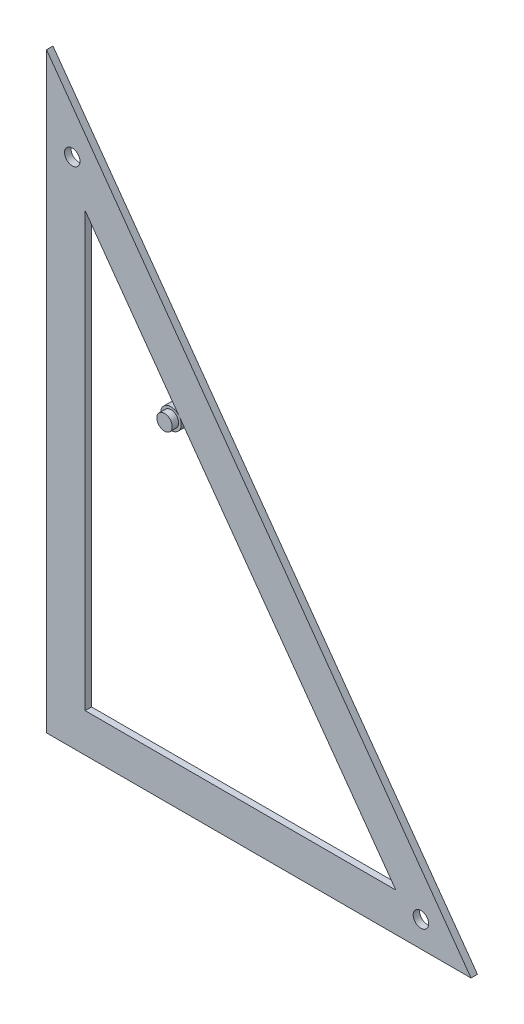
SolidWorks part; units mm, degrees
ref_plane "前视基准面" through (0, 0, 0) normal (0, 0, 1) x (1, 0, 0)
ref_plane "上视基准面" through (0, 0, 0) normal (0, 1, 0) x (1, 0, 0)
ref_plane "右视基准面" through (0, 0, 0) normal (1, 0, 0) x (0, 0, -1)
sketch "草图1" plane through (0, 0, 0) normal (0, 0, 1) x (1, 0, 0)
  line L0 (0, 0) -> (0, 460)
  line L1 (0, 460) -> (330, 0)
  line L2 (330, 0) -> (0, 0)
  line L3 (30, 30) -> (30, 366.7157)
  line L4 (30, 366.7157) -> (271.5569, 30)
  line L5 (271.5569, 30) -> (30, 30)
  circle A0 centre (20, 397.8105) radius 6
  circle A1 centre (291.0379, 20) radius 6
  dimension "D4" = 12
  dimension "D7" = 12
  dimension "D9" = 20
  dimension "D1" = 460
  dimension "D2" = 330
  dimension "D5" = 20
  dimension "D6" = 20
  dimension "D8" = 20
  dimension "D3" = 30
extrude "凸台-拉伸1" add sketch "草图1" along normal mid plane 5
sketch "草图2" plane through (0, 0, 0) normal (0, 0, 1) x (1, 0, 0)
  line L2 (271.5569, 30) -> (30, 366.7157) construction
  circle A0 centre (96.7112, 260) radius 8
  dimension "D1" = 16
  dimension "D2" = 200
extrude "凸台-拉伸2" add sketch "草图2" along normal mid plane 5 separate body
sketch "草图3" plane through (0, 0, 0) normal (0, 0, 1) x (1, 0, 0)
  circle A0 centre (96.7112, 260) radius 6
  dimension "D1" = 12
extrude "凸台-拉伸3" add sketch "草图3" along normal mid plane 15
